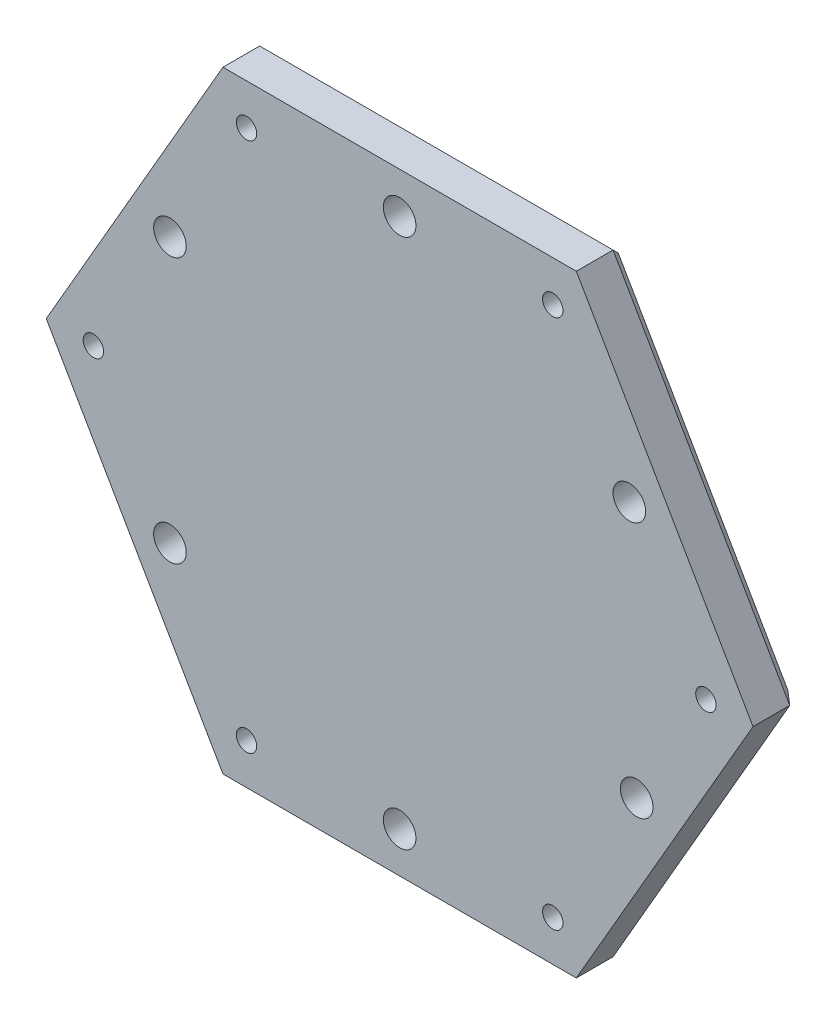
SolidWorks part; units mm, degrees
ref_plane "Front Plane" through (0, 0, 0) normal (1, 0, 0) x (0, 1, 0)
ref_plane "Top Plane" through (0, 0, 0) normal (0, 0, 1) x (0, 1, 0)
ref_plane "Right Plane" through (0, 0, 0) normal (0, 1, 0) x (-1, 0, 0)
sketch "Sketch1" plane through (0, 0, 0) normal (0, 0, 1) x (0, 1, 0)
  line L1 (0, -86.6025) -> (75, -43.3013)
  line L2 (75, -43.3013) -> (75, 43.3013)
  line L3 (75, 43.3013) -> (0, 86.6025)
  line L4 (0, 86.6025) -> (-75, 43.3013)
  line L5 (-75, 43.3013) -> (-75, -43.3013)
  line L6 (-75, -43.3013) -> (0, -86.6025)
  circle A0 centre (0, 0) radius 75 construction
  dimension "D1" = 150
extrude "Boss-Extrude1" add sketch "Sketch1" along normal mid plane 12
chamfer "Chamfer1" distance 3 angle 45 6 edges at (64.9519, 37.5, -6) (0, 75, -6) (-64.9519, 37.5, -6) (-64.9519, -37.5, -6) (0, -75, -6) (64.9519, -37.5, -6)
sketch "Sketch2" plane through (0, 0, 6) normal (0, 0, 1) x (1, 0, 0)
  line L1 (75.0555, 0) -> (37.5278, 65)
  line L2 (37.5278, 65) -> (-37.5278, 65)
  line L3 (-37.5278, 65) -> (-75.0555, 0)
  line L4 (-75.0555, 0) -> (-37.5278, -65)
  line L5 (-37.5278, -65) -> (37.5278, -65)
  line L6 (37.5278, -65) -> (75.0555, 0)
  circle A0 centre (0, 0) radius 65 construction
  point P13 (-56.2917, 32.5)
  point P15 (0, 65)
  point P17 (56.2917, 32.5)
  point P19 (56.2917, -32.5)
  point P21 (0, -65)
  point P23 (-56.2917, -32.5)
  dimension "D1" = 130
hole_wizard "M6 Tapped Hole1" positions "3DSketch1" profile "Sketch4" tap size "M6" standard "ISO" end condition through all
sketch3d "3DSketch1"
  point P0 (-37.5278, 65, 6)
  point P3 (37.5278, 65, 6)
  point P6 (75.0555, 0, 6)
  point P9 (37.5278, -65, 6)
  point P12 (-37.5278, -65, 6)
  point P15 (-75.0555, 0, 6)
sketch "Sketch4" plane through (-37.5278, 65, 6) normal (1, 0, 0) x (0, -1, 0)
  line L0 (0, 0) -> (0, 12)
  line L1 (0, 12) -> (2.5, 12)
  line L2 (2.5, 12) -> (2.5, 0)
  line L5 (2.5, 0) -> (0, 0)
  line L11 (0, -6.35) -> (0, 107.95) construction
  dimension "Thru Tap Drill Dia." = 5
  dimension "Thru Tap Drill Depth" = 12
cosmetic thread "Hole Thread1" parameters "D2"=6
cosmetic thread "Hole Thread2" parameters "D2"=6
cosmetic thread "Hole Thread3" parameters "D2"=6
cosmetic thread "Hole Thread4" parameters "D2"=6
cosmetic thread "Hole Thread5" parameters "D2"=6
cosmetic thread "Hole Thread6" parameters "D2"=6
hole_wizard "Ø8.0 (8) Diameter Hole2" positions "3DSketch3" profile "Sketch6" hole size "Ø8.0" standard "ISO" end condition through all
sketch3d "3DSketch3"
  line L0 (37.5278, -65, 6) -> (75.0555, 0, 6) construction
  point P0 (-56.2917, 32.5, 6)
  point P3 (0, 65, 6)
  point P6 (56.2917, 32.5, 6)
  point P9 (58.0963, -29.3742, 6)
  point P13 (0, -65, 6)
  point P16 (-56.2917, -32.5, 6)
sketch "Sketch6" plane through (-56.2917, 32.5, 6) normal (1, 0, 0) x (0, -1, 0)
  line L0 (0, 0) -> (0, 12)
  line L1 (0, 12) -> (4, 12)
  line L2 (4, 12) -> (4, 0)
  line L5 (4, 0) -> (0, 0)
  line L11 (0, -6.35) -> (0, 107.95) construction
  dimension "Thru Hole Dia." = 8
  dimension "Thru Hole Depth" = 12
